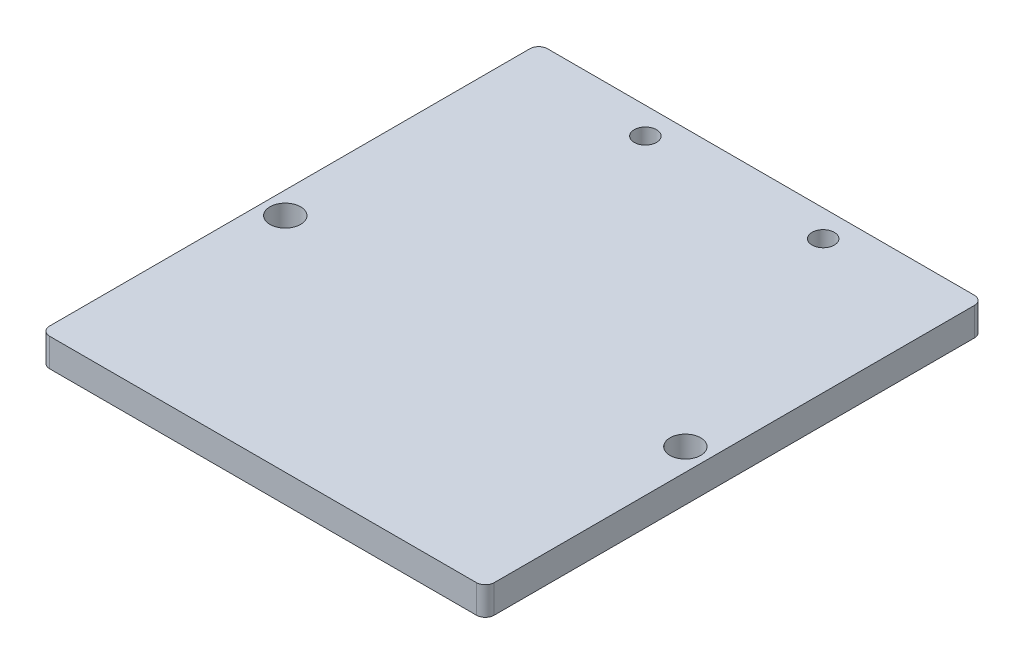
SolidWorks part; units mm, degrees
ref_plane "Front Plane" through (0, 0, 0) normal (0, 0, 1) x (1, 0, 0)
ref_plane "Top Plane" through (0, 0, 0) normal (0, 1, 0) x (1, 0, 0)
ref_plane "Right Plane" through (0, 0, 0) normal (1, 0, 0) x (0, 0, -1)
sketch "Sketch1" plane through (0, 0, 0) normal (0, 1, 0) x (1, 0, 0)
  line L1 (0, 0) -> (50, 0)
  line L2 (0, 0) -> (0, -56)
  line L3 (0, -56) -> (50, -56)
  line L4 (50, 0) -> (50, -56)
  circle A0 centre (15, -3) radius 1.1
  circle A1 centre (35, -3) radius 1.1
  dimension "D4" = 2.2
  dimension "D1" = 56
  dimension "D2" = 20
  dimension "D5" = 50
  dimension "D6" = 15
  dimension "D3" = 3
extrude "Boss-Extrude1" add sketch "Sketch1" along normal blind 3.175
fillet "Fillet1" radius 1 4 edges at (0, 1.5875, 56) (50, 1.5875, 56) (50, 1.5875, 0) (0, 1.5875, 0)
hole_wizard "M3x0.5 Tapped Hole1" positions "3DSketch1" profile "Sketch2" tap size "M3x0.5" standard "ANSI Metric" end condition through all
sketch3d "3DSketch1"
  circle A0 centre (35, 3.175, 3) radius 1.1 construction
  circle A1 centre (15, 3.175, 3) radius 1.1 construction
  point P0 (15, 3.175, 3)
  point P2 (35, 3.175, 3)
  point P7 (35, 4.275, 3)
  point P11 (15, 4.275, 3)
sketch "Sketch2" plane through (15, 3.175, 3) normal (1, 0, 0) x (0, 0, 1)
  line L0 (0, 0) -> (0, 3.175)
  line L1 (0, 3.175) -> (1.25, 3.175)
  line L2 (1.25, 3.175) -> (1.25, 0)
  line L5 (1.25, 0) -> (0, 0)
  line L11 (0, -6.35) -> (0, 107.95) construction
  dimension "Thru Tap Drill Dia." = 2.5
  dimension "Thru Tap Drill Depth" = 3.175
cosmetic thread "Hole Thread1" parameters "D2"=3
cosmetic thread "Hole Thread2" parameters "D2"=3
sketch "Sketch3" plane through (0, 3.175, 0) normal (0, 1, 0) x (1, 0, 0)
  line L0 (2.5, -31) -> (47.5, -31) construction
  line L1 (0, -1) -> (0, -55) construction
  line L2 (50, -55) -> (50, -1) construction
  line L3 (1, -56) -> (49, -56) construction
  circle A0 centre (2.5, -31) radius 1.725
  circle A1 centre (47.5, -31) radius 1.725
  dimension "D1" = 3.45
  dimension "D2" = 2.5
  dimension "D3" = 2.5
  dimension "D4" = 25
  dimension "D5" = 45
extrude "Cut-Extrude1" cut sketch "Sketch3" against normal through all both
equation "\"D6@Sketch1\"=(\"D5@Sketch1\"-\"D2@Sketch1\")/2"
equation "\"D3@Sketch3\"=\"D2@Sketch3\""
